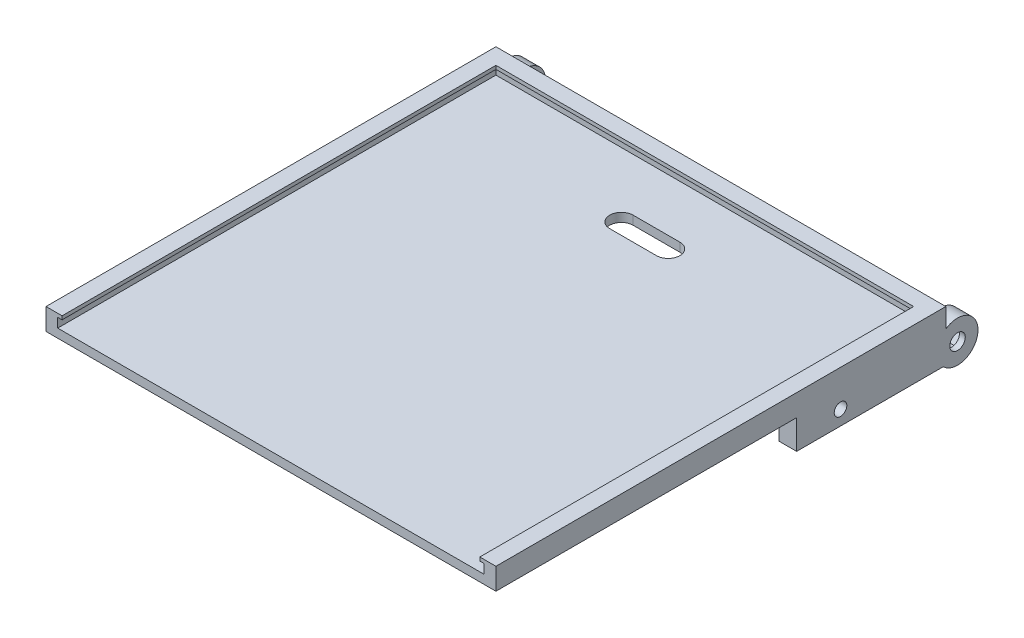
SolidWorks part; units mm, degrees
ref_plane "Front Plane" through (0, 0, 0) normal (0, 0, 1) x (1, 0, 0)
ref_plane "Top Plane" through (0, 0, 0) normal (0, 1, 0) x (1, 0, 0)
ref_plane "Right Plane" through (0, 0, 0) normal (1, 0, 0) x (0, 0, -1)
ref_plane "Plano_Top Plane_+5" through (0, 5, 0) normal (0, 1, 0) x (1, 0, 0)
sketch "Croquis_placa" plane through (0, 5, 0) normal (0, 1, 0) x (1, 0, 0)
  line L1 (-76.9, -157.8) -> (76.9, -157.8)
  line L2 (-76.9, -157.8) -> (-76.9, -4)
  line L3 (-76.9, -4) -> (76.9, -4)
  line L4 (76.9, -157.8) -> (76.9, -4)
  line L5 (-76.9, -157.8) -> (76.9, -4) construction
  line L6 (-76.9, -4) -> (76.9, -157.8) construction
  point P0 (0, -80.9)
  dimension "D1" = 153.8
  dimension "D2" = 153.8
extrude "Placa" add sketch "Croquis_placa" along normal blind 3
ref_plane "Plano_Top Plane_+8" through (0, 8, 0) normal (0, 1, 0) x (1, 0, 0)
sketch "Croquis_Borde_izq" plane through (0, 8, 0) normal (0, 1, 0) x (1, 0, 0)
  line L0 (76.9, -4) -> (-76.9, -4) construction
  line L1 (-76.9, -157.8) -> (-72.9, -157.8)
  line L2 (-76.9, -157.8) -> (-76.9, -4)
  line L3 (-76.9, -4) -> (-72.9, -4)
  line L4 (-72.9, -157.8) -> (-72.9, -4)
  line L5 (-76.9, -157.8) -> (-72.9, -4) construction
  line L6 (-76.9, -4) -> (-72.9, -157.8) construction
  point P0 (-74.9, -80.9)
extrude "Borde_izq" add sketch "Croquis_Borde_izq" along normal blind 3.2
sketch "Croquis_Borde_der" plane through (0, 8, 0) normal (0, 1, 0) x (1, 0, 0)
  line L1 (72.9, -157.8) -> (76.9, -157.8)
  line L2 (72.9, -157.8) -> (72.9, -4)
  line L3 (72.9, -4) -> (76.9, -4)
  line L4 (76.9, -157.8) -> (76.9, -4)
  line L5 (72.9, -157.8) -> (76.9, -4) construction
  line L6 (72.9, -4) -> (76.9, -157.8) construction
  point P0 (74.9, -80.9)
extrude "Borde_der" add sketch "Croquis_Borde_der" along normal blind 3.2
sketch "Croquis_Borde_tras" plane through (0, 8, 0) normal (0, 1, 0) x (1, 0, 0)
  line L1 (-72.9, -8) -> (72.9, -8)
  line L2 (-72.9, -8) -> (-72.9, -4)
  line L3 (-72.9, -4) -> (72.9, -4)
  line L4 (72.9, -8) -> (72.9, -4)
  line L5 (-72.9, -8) -> (72.9, -4) construction
  line L6 (-72.9, -4) -> (72.9, -8) construction
  point P0 (0, -6)
extrude "Borde_tras" add sketch "Croquis_Borde_tras" along normal blind 3.2
ref_plane "Plano_Top Plane_+11_2" through (0, 11.2, 0) normal (0, 1, 0) x (1, 0, 0)
sketch "Croquis_Ceja_izq" plane through (0, 11.2, 0) normal (0, 1, 0) x (1, 0, 0)
  line L0 (76.9, -4) -> (-76.9, -4) construction
  line L1 (-76.9, -157.8) -> (-71.4, -157.8)
  line L2 (-76.9, -157.8) -> (-76.9, -4)
  line L3 (-76.9, -4) -> (-71.4, -4)
  line L4 (-71.4, -157.8) -> (-71.4, -4)
  line L5 (-76.9, -157.8) -> (-71.4, -4) construction
  line L6 (-76.9, -4) -> (-71.4, -157.8) construction
  point P0 (-74.15, -80.9)
extrude "Ceja_izq" add sketch "Croquis_Ceja_izq" along normal blind 1.2
sketch "Croquis_Ceja_der" plane through (0, 11.2, 0) normal (0, 1, 0) x (1, 0, 0)
  line L1 (71.4, -157.8) -> (76.9, -157.8)
  line L2 (71.4, -157.8) -> (71.4, -4)
  line L3 (71.4, -4) -> (76.9, -4)
  line L4 (76.9, -157.8) -> (76.9, -4)
  line L5 (71.4, -157.8) -> (76.9, -4) construction
  line L6 (71.4, -4) -> (76.9, -157.8) construction
  point P0 (74.15, -80.9)
extrude "Ceja_der" add sketch "Croquis_Ceja_der" along normal blind 1.2
sketch "Croquis_Ceja_tras" plane through (0, 11.2, 0) normal (0, 1, 0) x (1, 0, 0)
  line L0 (76.9, -4) -> (71.4, -4) construction
  line L1 (-74.15, -9.5) -> (74.15, -9.5)
  line L2 (-74.15, -9.5) -> (-74.15, -4)
  line L3 (-74.15, -4) -> (74.15, -4)
  line L4 (74.15, -9.5) -> (74.15, -4)
  line L5 (-74.15, -9.5) -> (74.15, -4) construction
  line L6 (-74.15, -4) -> (74.15, -9.5) construction
extrude "Ceja_tras" add sketch "Croquis_Ceja_tras" along normal blind 1.2
sketch "Croquis_cable" plane through (0, 0, 0) normal (0, 1, 0) x (1, 0, 0)
  line L0 (-8, -30) -> (8, -30) construction
  line L1 (-8, -26) -> (8, -26)
  line L2 (-8, -34) -> (8, -34)
  arc A0 (-8, -26) -> (-8, -34) centre (-8, -30) ccw
  arc A1 (8, -34) -> (8, -26) centre (8, -30) ccw
  point P2 (0, -30)
  point P7 (0, 0)
extrude "Paso_cable" cut sketch "Croquis_cable" along normal through all and the other way through all
sketch "Croquis_refuerzos" plane through (0, 5, 0) normal (0, 1, 0) x (1, 0, 0)
  line L1 (-41.5, -150) -> (-38.5, -150)
  line L2 (-41.5, -150) -> (-41.5, -8)
  line L3 (-41.5, -8) -> (-38.5, -8)
  line L4 (-38.5, -150) -> (-38.5, -8)
  line L5 (-41.5, -150) -> (-38.5, -8) construction
  line L6 (-41.5, -8) -> (-38.5, -150) construction
  line L7 (38.5, -150) -> (41.5, -150)
  line L8 (38.5, -150) -> (38.5, -8)
  line L9 (38.5, -8) -> (41.5, -8)
  line L10 (41.5, -150) -> (41.5, -8)
  line L11 (38.5, -150) -> (41.5, -8) construction
  line L12 (38.5, -8) -> (41.5, -150) construction
  point P0 (40, -79)
  dimension "D1" = 3
  dimension "D2" = 142
extrude "Refuerzos" add sketch "Croquis_refuerzos" against normal blind 5
ref_plane "Plano_Right Plane_+70_9" through (70.9, 0, 0) normal (1, 0, 0) x (0, 0, -1)
sketch "Croquis_costilla_der" plane through (70.9, 0, 0) normal (1, 0, 0) x (0, 0, -1)
  line L1 (-55, -5) -> (0, -5)
  line L2 (-55, -5) -> (-55, 5)
  line L3 (-55, 5) -> (0, 5)
  line L4 (0, -5) -> (0, 5)
  line L5 (-55, -5) -> (0, 5) construction
  line L6 (-55, 5) -> (0, -5) construction
  dimension "D1" = 55
  dimension "D2" = 10
extrude "Costilla_der" add sketch "Croquis_costilla_der" along normal blind 6
sketch "Croquis_buje_der" plane through (70.9, 0, 0) normal (1, 0, 0) x (0, 0, -1)
  circle A0 centre (0, 0) radius 7
  dimension "D1" = 14
extrude "Buje_der" add sketch "Croquis_buje_der" along normal blind 6
ref_plane "Plano_Right Plane_-70_9" through (-70.9, 0, 0) normal (1, 0, 0) x (0, 0, -1)
sketch "Croquis_costilla_izq" plane through (-70.9, 0, 0) normal (1, 0, 0) x (0, 0, -1)
  line L1 (-55, -5) -> (0, -5)
  line L2 (-55, -5) -> (-55, 5)
  line L3 (-55, 5) -> (0, 5)
  line L4 (0, -5) -> (0, 5)
  line L5 (-55, -5) -> (0, 5) construction
  line L6 (-55, 5) -> (0, -5) construction
extrude "Costilla_izq" add sketch "Croquis_costilla_izq" against normal blind 6
sketch "Croquis_buje_izq" plane through (-70.9, 0, 0) normal (1, 0, 0) x (0, 0, -1)
  circle A0 centre (0, 0) radius 7
extrude "Buje_izq" add sketch "Croquis_buje_izq" against normal blind 6
sketch "Croquis_agujeros_eje" plane through (0, 0, 0) normal (1, 0, 0) x (0, 0, -1)
  circle A0 centre (0, 0) radius 2.65
  circle A1 centre (-40, 0) radius 2.15
  dimension "D1" = 5.3
  dimension "D2" = 4.3
extrude "Agujeros_pivote_y_bloqueo" cut sketch "Croquis_agujeros_eje" along normal through all and the other way through all
sketch "Croquis_tuerca_M5_der" plane through (70.9, 0, 0) normal (1, 0, 0) x (0, 0, -1)
  line L0 (4.7343, 0) -> (2.3671, 4.1)
  line L1 (2.3671, 4.1) -> (-2.3671, 4.1)
  line L2 (-2.3671, 4.1) -> (-4.7343, 0)
  line L3 (-4.7343, 0) -> (-2.3671, -4.1)
  line L4 (-2.3671, -4.1) -> (2.3671, -4.1)
  line L5 (2.3671, -4.1) -> (4.7343, 0)
extrude "Tuerca_M5_der" cut sketch "Croquis_tuerca_M5_der" along normal blind 4
sketch "Croquis_tuercas_izq" plane through (-70.9, 0, 0) normal (1, 0, 0) x (0, 0, -1)
  line L0 (4.7343, 0) -> (2.3671, 4.1)
  line L1 (2.3671, 4.1) -> (-2.3671, 4.1)
  line L2 (-2.3671, 4.1) -> (-4.7343, 0)
  line L3 (-4.7343, 0) -> (-2.3671, -4.1)
  line L4 (-2.3671, -4.1) -> (2.3671, -4.1)
  line L5 (2.3671, -4.1) -> (4.7343, 0)
  line L6 (-35.8431, 0) -> (-37.9215, 3.6)
  line L7 (-37.9215, 3.6) -> (-42.0785, 3.6)
  line L8 (-42.0785, 3.6) -> (-44.1569, 0)
  line L9 (-44.1569, 0) -> (-42.0785, -3.6)
  line L10 (-42.0785, -3.6) -> (-37.9215, -3.6)
  line L11 (-37.9215, -3.6) -> (-35.8431, 0)
extrude "Tuercas_M5_M4_izq" cut sketch "Croquis_tuercas_izq" against normal blind 4
